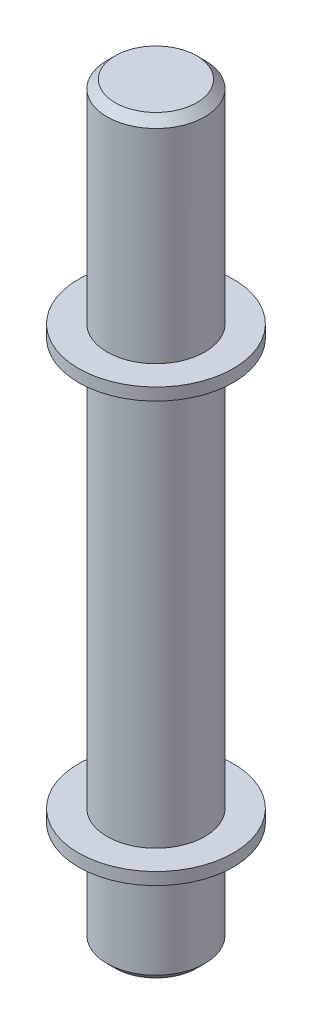
SolidWorks part; units mm, degrees
ref_plane "Front Plane" through (0, 0, 0) normal (0, 0, 1) x (1, 0, 0)
ref_plane "Top Plane" through (0, 0, 0) normal (0, 1, 0) x (1, 0, 0)
ref_plane "Right Plane" through (0, 0, 0) normal (1, 0, 0) x (0, 0, -1)
sketch "Sketch2" plane through (0, 0, 0) normal (1, 0, 0) x (0, 0, -1)
  line L0 (0, 29.7776) -> (0, 0) construction
  line L1 (0, 0) -> (12, 0)
  line L2 (12, 0) -> (12, 26)
  line L3 (12, 26) -> (19, 26)
  line L4 (19, 26) -> (19, 29)
  line L5 (19, 29) -> (12, 29)
  line L6 (12, 29) -> (12, 129)
  line L7 (12, 129) -> (19, 129)
  line L8 (19, 129) -> (19, 132)
  line L9 (19, 132) -> (12, 132)
  line L10 (12, 132) -> (12, 184)
  line L11 (12, 184) -> (0, 184)
  line L12 (0, 184) -> (0, 0)
  dimension "D1" = 12
  dimension "D2" = 19
  dimension "D3" = 3
  dimension "D4" = 26
  dimension "D5" = 52
  dimension "D6" = 100
revolve "Revolve2" add sketch "Sketch2" angle 360 about L0
cosmetic thread "Cosmetic Thread1" parameters "D1"=26, "D2"=20.704
cosmetic thread "Cosmetic Thread2" parameters "D1"=26, "D2"=6.619
chamfer "Chamfer1" distance 2 angle 45 2 edges at (0, 0, 12) (0, 184, 12)
